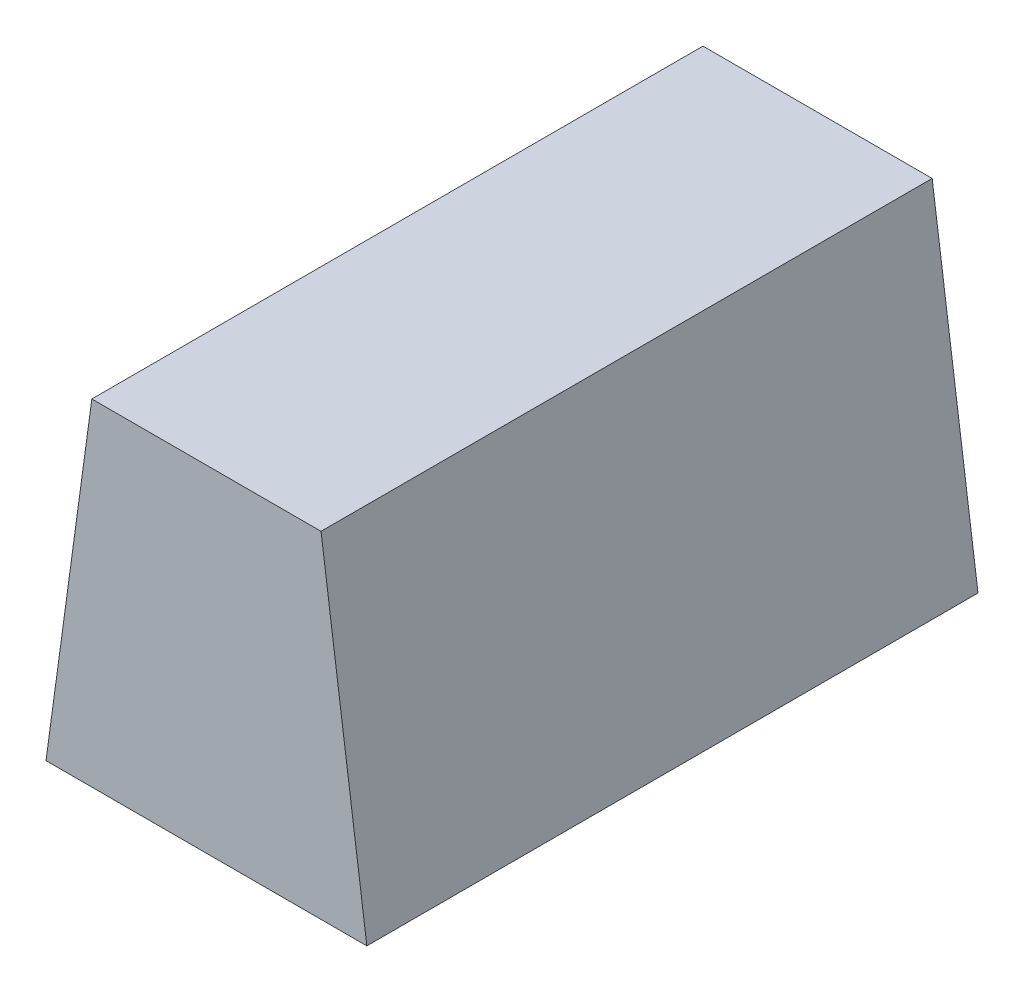
SolidWorks part; units mm, degrees
ref_plane "Alzado" through (0, 0, 0) normal (0, 0, 1) x (1, 0, 0)
ref_plane "Planta" through (0, 0, 0) normal (0, 1, 0) x (1, 0, 0)
ref_plane "Vista lateral" through (0, 0, 0) normal (1, 0, 0) x (0, 0, -1)
sketch "Croquis1" plane through (0, 0, 0) normal (0, 0, 1) x (1, 0, 0)
  line L0 (0, 0) -> (21, 0)
  line L1 (21, 0) -> (18, 22)
  line L2 (18, 22) -> (3, 22)
  line L3 (3, 22) -> (0, 0)
  line L4 (10.5, 22) -> (10.5, 0) construction
  dimension "D1" = 15
  dimension "D2" = 21
  dimension "D3" = 22
extrude "Saliente-Extruir1" add sketch "Croquis1" along normal blind 40
